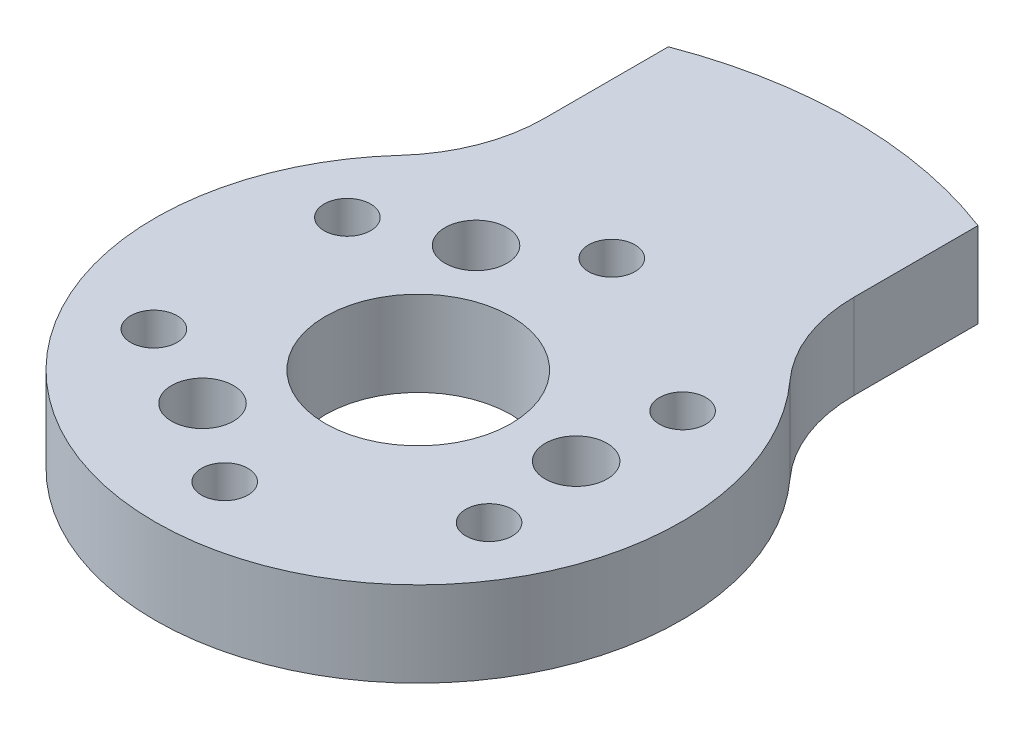
SolidWorks part; units mm, degrees
ref_plane "前视基准面" through (0, 0, 0) normal (0, 0, 1) x (1, 0, 0)
ref_plane "上视基准面" through (0, 0, 0) normal (0, 1, 0) x (1, 0, 0)
ref_plane "右视基准面" through (0, 0, 0) normal (1, 0, 0) x (0, 0, -1)
other "Configuration Table"
sketch "草图1" plane through (0, 0, 0) normal (0, 1, 0) x (1, 0, 0)
  line L0 (0, -12.5) -> (0, 23.9769) construction
  line L5 (-10, 26.1534) -> (-10, 13.7477)
  line L6 (10, 26.1534) -> (10, 13.7477)
  arc A0 (-10, 13.7477) -> (10, 13.7477) centre (0, 0) ccw
  circle A1 centre (-5.1, 8.8335) radius 2
  circle A2 centre (-10.8253, 6.25) radius 1.5
  circle A3 centre (10.2, 0) radius 2
  circle A4 centre (-5.1, -8.8335) radius 2
  circle A5 centre (0, 12.5) radius 1.5
  circle A6 centre (10.8253, 6.25) radius 1.5
  circle A7 centre (10.8253, -6.25) radius 1.5
  circle A8 centre (0, -12.5) radius 1.5
  circle A9 centre (-10.8253, -6.25) radius 1.5
  circle A10 centre (0, 0) radius 6
  arc A13 (10, 26.1534) -> (-10, 26.1534) centre (0, 0) ccw
  point P13 (0, 0)
  point P24 (0, 0)
  dimension "D1" = 3
  dimension "D2" = 6
extrude "凸台-拉伸1" add sketch "草图1" along normal blind 5.5
fillet "圆角1" radius 10 2 edges at (-10, 2.75, -13.7477) (10, 2.75, -13.7477)
